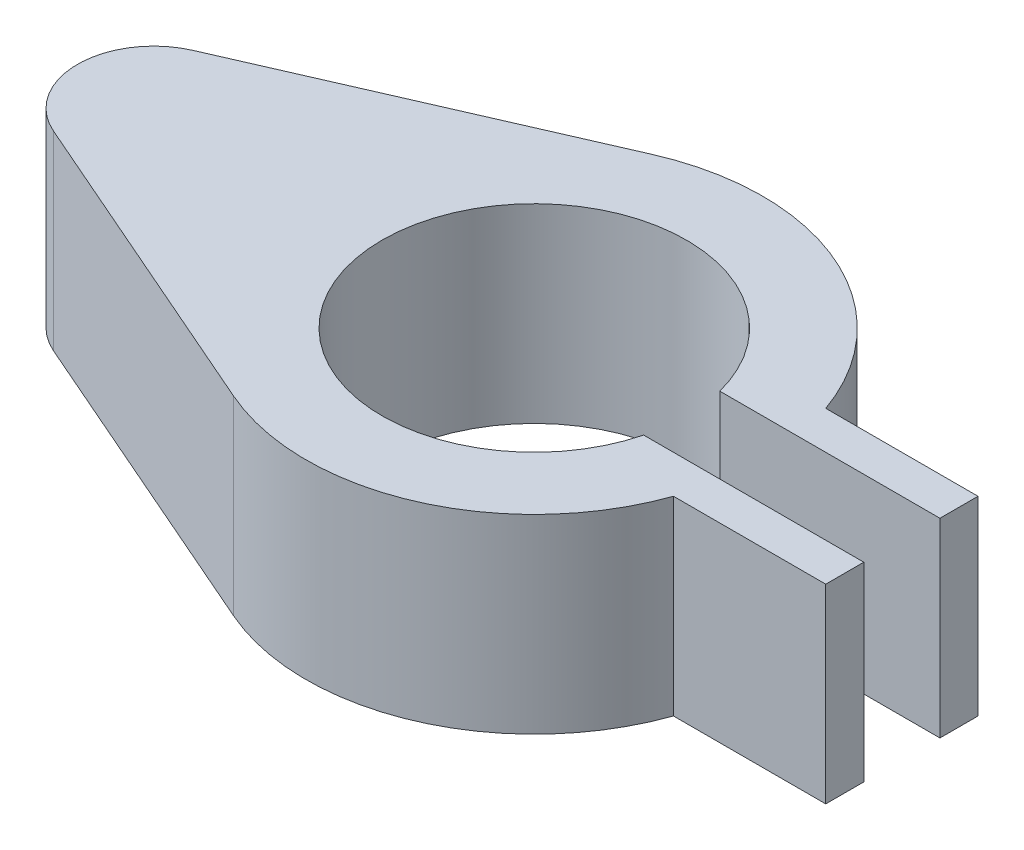
SolidWorks part; units mm, degrees
ref_plane "Plano frontal" through (0, 0, 0) normal (0, 0, 1) x (1, 0, 0)
ref_plane "Plano superior" through (0, 0, 0) normal (0, 1, 0) x (1, 0, 0)
ref_plane "Plano direito" through (0, 0, 0) normal (1, 0, 0) x (0, 0, -1)
sketch "Esboço2" plane through (0, 0, 0) normal (0, 1, 0) x (1, 0, 0)
  line L0 (6.9645, 0) -> (-19.1106, 0) construction
  line L1 (-2.4, 5.4991) -> (-10.8, 1.833)
  line L2 (-10.8, -1.833) -> (-2.4, -5.4991)
  circle A0 centre (0, 0) radius 4
  circle A1 centre (0, 0) radius 6
  circle A2 centre (-10, 0) radius 2
  dimension "D1" = 12
  dimension "D2" = 8
  dimension "D3" = 4
  dimension "D4" = 10
extrude "Ressalto-extrusão1" add sketch "Esboço2" along normal blind 5 contours A1 L0 A0 | A1 L0 A2 L2 | L0 A1 L1 A2 | L0 A1 A0 | A2 L0 | L0 A2
sketch "Esboço3" plane through (0, 5, 0) normal (0, 1, 0) x (1, 0, 0)
  line L0 (-0.8453, 0) -> (22.133, 0) construction
  line L2 (5.6569, 2) -> (9.6569, 2)
  line L3 (5.6569, 2) -> (5.6569, -2)
  line L4 (5.6569, -2) -> (9.6569, -2)
  line L5 (9.6569, 2) -> (9.6569, -2)
  arc A0 (-2.4, -5.4991) -> (-2.4, 5.4991) centre (0, 0) ccw construction
  dimension "D1" = 4
  dimension "D2" = 4
  dimension "D3" = 2
extrude "Ressalto-extrusão2" add sketch "Esboço3" against normal through all
sketch "Esboço5" plane through (0, 5, 0) normal (0, 1, 0) x (1, 0, 0)
  line L0 (-0.5857, 0) -> (12.9496, 0) construction
  line L2 (2.3215, 1) -> (11.4245, 1)
  line L3 (2.3215, 1) -> (2.3215, -1)
  line L4 (2.3215, -1) -> (11.4245, -1)
  line L5 (11.4245, 1) -> (11.4245, -1)
  line L6 (2.3215, 1) -> (11.4245, -1) construction
  line L7 (2.3215, -1) -> (11.4245, 1) construction
  point P3 (6.873, 0)
  dimension "D1" = 2
extrude "Corte-extrusão1" cut sketch "Esboço5" against normal blind 5
